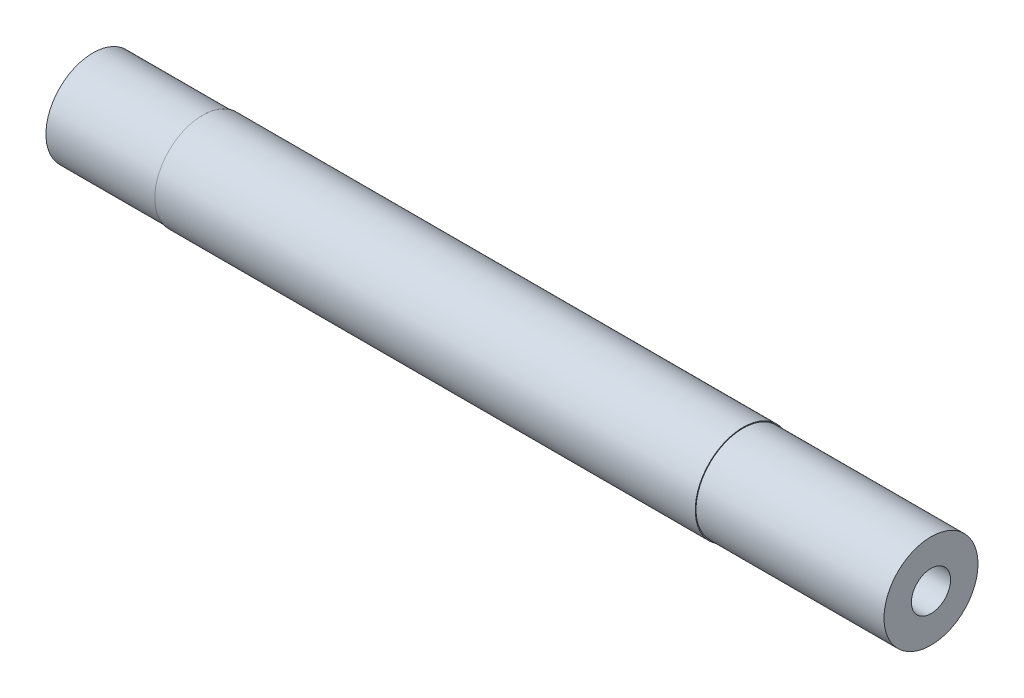
SolidWorks part; units mm, degrees
material "AISI 1020"
ref_plane "Front Plane" through (0, 0, 0) normal (0, 0, 1) x (1, 0, 0)
ref_plane "Top Plane" through (0, 0, 0) normal (0, 1, 0) x (1, 0, 0)
ref_plane "Right Plane" through (0, 0, 0) normal (1, 0, 0) x (0, 0, -1)
sketch "Sketch1" plane through (0, 0, 0) normal (0, 1, 0) x (1, 0, 0)
  line L0 (0, 0) -> (-9.079, 0) construction
  line L1 (0, 0) -> (7, 0)
  line L2 (0, 0) -> (0, 3)
  line L3 (0, 3) -> (7, 3)
  line L5 (7, 0) -> (41.5, 0)
  line L6 (7, 3) -> (7, 3.05)
  line L7 (7, 3.05) -> (41.5, 3.05)
  line L8 (41.5, 3) -> (41.5, 3.05)
  line L9 (41.5, 0) -> (53.5, 0)
  line L11 (41.5, 3) -> (53.5, 3)
  line L12 (53.5, 0) -> (53.5, 3)
  dimension "D1" = 6
  dimension "D2" = 7
  dimension "D3" = 6.1
  dimension "D4" = 34.5
  dimension "D5" = 12
  dimension "D6" = 53.5
revolve "Revolve1" add sketch "Sketch1" angle 360 about L0
cosmetic thread "Representação de rosca1" parameters "D2"=4.891
cosmetic thread "Representação de rosca2" parameters "D2"=4.891
sketch "Esboço1" plane through (53.5, 0, 0) normal (1, 0, 0) x (0, 0, -1)
  circle A0 centre (0, 0) radius 1.25
  dimension "D1" = 2.5
extrude "Corte-extrusão1" cut sketch "Esboço1" against normal blind 10
